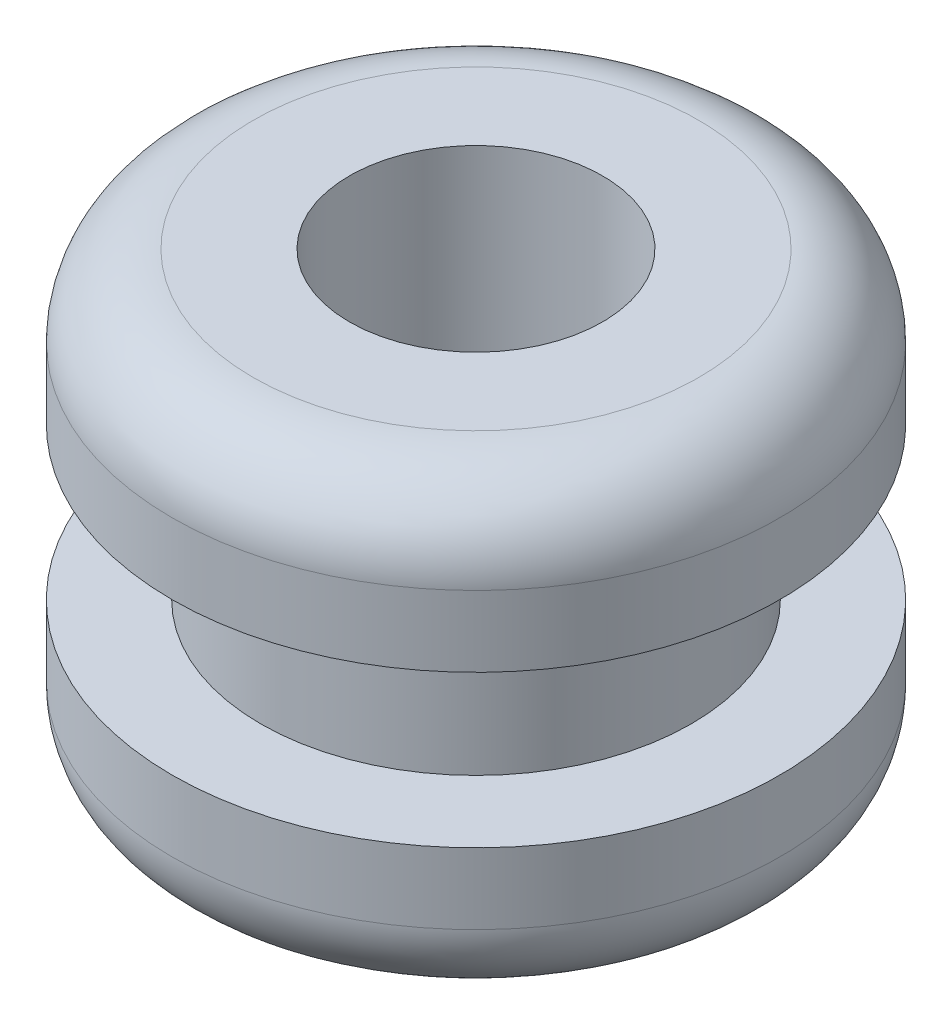
SolidWorks part; units mm, degrees
material "Rubber"
ref_plane "Front Plane" through (0, 0, 0) normal (0, 0, 1) x (1, 0, 0)
ref_plane "Top Plane" through (0, 0, 0) normal (0, 1, 0) x (1, 0, 0)
ref_plane "Right Plane" through (0, 0, 0) normal (1, 0, 0) x (0, 0, -1)
sketch "Sketch2" plane through (0, 0, 0) normal (0, 1, 0) x (1, 0, 0)
  circle A0 centre (0, 0) radius 9.525
  dimension "D1" = 19.05
extrude "Boss-Extrude1" add sketch "Sketch2" along normal mid plane 14.2875
sketch "Sketch3" plane through (0, 0, 0) normal (0, 1, 0) x (1, 0, 0)
  circle A0 centre (0, 0) radius 9.525
  circle A1 centre (0, 0) radius 6.7469
  dimension "D1" = 19.05
  dimension "D2" = 13.4937
extrude "Cut-Extrude1" cut sketch "Sketch3" against normal mid plane 4.7625
fillet "Fillet1" radius 2.54 2 edges at (0, -7.1437, 9.525) (0, 7.1437, 9.525)
sketch "Sketch4" plane through (0, 7.1437, 0) normal (0, 1, 0) x (1, 0, 0)
  circle A0 centre (0, 0) radius 3.9688
  dimension "D1" = 7.9375
extrude "Cut-Extrude2" cut sketch "Sketch4" against normal through all
